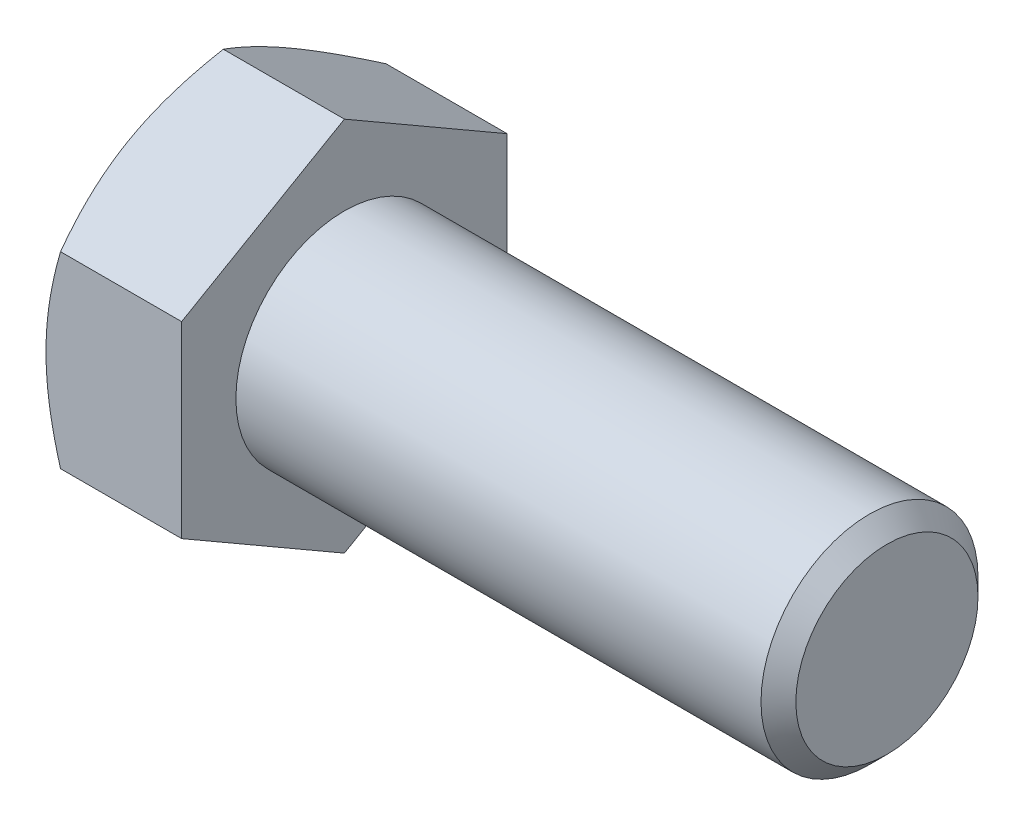
SolidWorks part; units mm, degrees
extrude "BaseHead" add sketch "Sketch1" along normal blind 7.5
sketch "Sketch1" plane through (0, 0, 0) normal (1, 0, 0) x (0, 0, -1)
  line L0 (9, 5.1962) -> (9, -5.1962)
  line L1 (-9, 5.1962) -> (-9, -5.1962)
  line L2 (9, -5.1962) -> (0, -10.3923)
  line L3 (0, -10.3923) -> (-9, -5.1962)
  line L4 (9, 5.1962) -> (0, 10.3923)
  line L5 (0, 10.3923) -> (-9, 5.1962)
  dimension "Width_flats" = 18
  dimension "D2" = 120
  dimension "D3" = 9
  dimension "D4" = 9
  dimension "D5" = 9
ref_plane "Plane1" through (0, 0, 0) normal (0, 0, 1) x (1, 0, 0)
ref_plane "Plane2" through (0, 0, 0) normal (0, 1, 0) x (1, 0, 0)
ref_plane "Plane3" through (0, 0, 0) normal (1, 0, 0) x (0, 0, -1)
sketch "BodySke" plane through (0, 0, 0) normal (0, 0, 1) x (1, 0, 0)
  line L1 (0, 0) -> (37.5, 0)
  line L2 (0, 0) -> (0, 6)
  line L4 (37.5, 0) -> (37.5, 5.036)
  line L5 (7.5, 10.3923) -> (7.5, 5.1962) construction
  line L6 (37.5, 5.036) -> (36.536, 6)
  line L7 (0, 0) -> (110.49, 0) construction
  line L8 (37.5, -5.036) -> (36.536, -6) construction
  line L9 (0, 5.1962) -> (0, -5.1962) construction
  line L10 (9.25, 15.24) -> (9.25, -1.27) construction
  line L11 (7.5, 15.24) -> (7.5, -1.27) construction
  line L12 (7.5, 5.1962) -> (7.5, -5.1962) construction
  line L15 (0, 6) -> (36.536, 6)
  dimension "Body_ch_ang" = 45
  dimension "Minor_dia" = 10.072
  dimension "Diameter" = 12
revolve "BaseBody" add sketch "BodySke" angle 360 about L7
cosmetic thread "ThreadCosmetic" [suppressed] parameters "Thread_length"=28.25, "Thread_minor"=10.072
fillet "HeadFillet" [suppressed] radius 0.6
sketch "Sketch3" plane through (0, 0, 0) normal (0, 0, 1) x (1, 0, 0)
  line L0 (0, 9) -> (3.6906, 15.3923)
  line L1 (0, 10.3923) -> (0, 5.1962) construction
  line L2 (3.6906, 15.3923) -> (3.6906, 20.3923)
  line L3 (3.6906, 20.3923) -> (-10, 20.3923)
  line L4 (-10, 20.3923) -> (-10, 9)
  line L5 (-10, 9) -> (0, 9)
  line L6 (0, 0) -> (99.06, 0) construction
  line L7 (7.5, 10.3923) -> (0, 10.3923) construction
  dimension "D1" = 9
  dimension "D2" = 5
  dimension "D3" = 10
  dimension "D4" = 5
  dimension "Head_ch_ang" = 30
revolve "HeadChamfer" cut sketch "Sketch3" angle 360 about L6
sketch "ThdSchSke" plane through (0, 0, 0) normal (0, 0, 1) x (1, 0, 0)
  line L0 (9.25, -5.036) -> (8.575, -6)
  line L1 (9.25, -5.036) -> (9.925, -6)
  line L2 (9.925, -6) -> (9.925, -7.5)
  line L3 (-3.175, 0) -> (5.1513, 0) construction
  line L5 (9.925, -7.5) -> (8.575, -7.5)
  line L6 (8.575, -7.5) -> (8.575, -6)
  dimension "Thread_minor" = 10.072
  dimension "Diameter" = 12
  dimension "Start" = 9.25
revolve "ThreadSchematic" [suppressed] cut sketch "ThdSchSke" angle 360 about L3
pattern_linear "ThdSchPat" [suppressed]
equation "\"D3@Sketch1\" = \"Width_flats@Sketch1\" / 2"
equation "\"D4@Sketch1\" = \"D3@Sketch1\""
equation "\"D5@Sketch1\" = \"D4@Sketch1\""
equation "\"Thread_minor@ThreadCosmetic\" = \"Minor_dia@BodySke\""
equation "\"D1@Sketch3\" = \"Width_flats@Sketch1\" / 2"
equation "\"Thread_length@ThreadCosmetic\" = ((sgn( (\"Length@BodySke\" - \"Advance@BodySke\" ) - \"Thread_nom@BodySke\" )-1)*( (\"Length@BodySke\" - \"Advance@BodySke\" ) - \"Thread_nom@BodySke\" ))/-2+ \"Thread_nom@BodySke\""
equation "\"Thread_minor@ThdSchSke\" = \"Minor_dia@BodySke\""
equation "\"Diameter@ThdSchSke\" = \"Diameter@BodySke\""
equation "\"Overcut@ThdSchSke\" = \"Diameter@BodySke\" * 1.25"
equation "\"Start@ThdSchSke\" = \"Head_ht@BaseHead\" + \"Length@BodySke\" - \"Thread_length@ThreadCosmetic\"  '---Non-countersunk---"
equation "\"Num_threads@ThdSchPat\" = int( \"Thread_length@ThreadCosmetic\" / \"Advance@BodySke\" + 0.999 )  + 1"
equation "\"Advance@ThdSchPat\" = \"Thread_length@ThreadCosmetic\" /  (\"Num_threads@ThdSchPat\" - 1) 'relax it"
equation "\"Num_threads@ThdSchPat\" = \"Num_threads@ThdSchPat\" - sgn( \"Num_threads@ThdSchPat\" - 1) '---chamfered tips only---"
